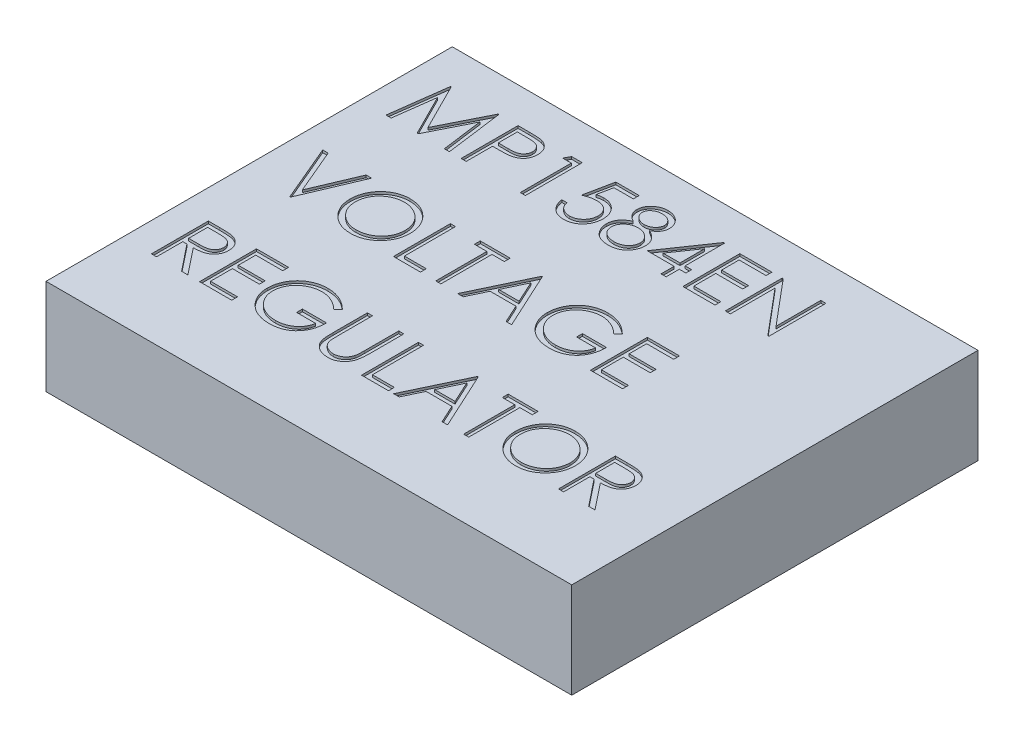
SolidWorks part; units mm, degrees
ref_plane "Front Plane" through (0, 0, 0) normal (0, 0, 1) x (1, 0, 0)
ref_plane "Top Plane" through (0, 0, 0) normal (0, 1, 0) x (1, 0, 0)
ref_plane "Right Plane" through (0, 0, 0) normal (1, 0, 0) x (0, 0, -1)
sketch "Sketch1" plane through (0, 0, 0) normal (0, 1, 0) x (1, 0, 0)
  line L1 (-11, -8.5) -> (11, -8.5)
  line L2 (-11, -8.5) -> (-11, 8.5)
  line L3 (-11, 8.5) -> (11, 8.5)
  line L4 (11, -8.5) -> (11, 8.5)
  line L5 (-11, -8.5) -> (11, 8.5) construction
  line L6 (-11, 8.5) -> (11, -8.5) construction
  point P0 (0, 0)
  dimension "D1" = 22
  dimension "D2" = 17
extrude "Boss-Extrude1" add sketch "Sketch1" along normal blind 4
sketch "Sketch2" plane through (0, 4, 0) normal (0, 1, 0) x (1, 0, 0)
  text T0 "MP1584EN\r\nVOLTAGE\r\nREGULATOR" font "Century Gothic" height in points 9
  point P1 (-11, 3.7032)
  point P2 (-11, 3.7032)
  point P3 (-9.896, 1.8047)
  point P4 (10.1088, 1.578)
  point P5 (-11, 4.4683)
  point P6 (-9.9243, 5.4033)
  point P7 (-10.0943, 4.6383)
  point P8 (0, 0)
  point P9 (-11, 5.6867)
  point P10 (0, 0)
extrude "Cut-Extrude1" cut sketch "Sketch2" against normal blind 0.1
